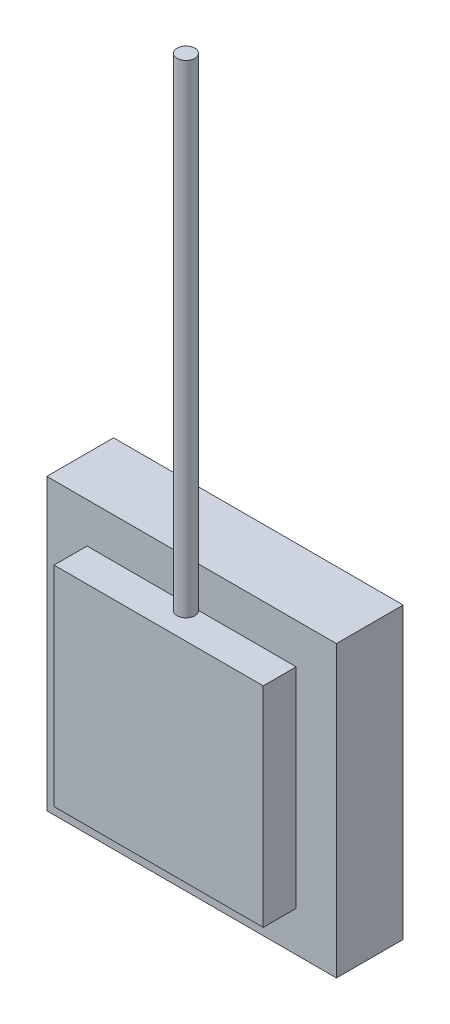
SolidWorks part; units mm, degrees
ref_plane "Спереди" through (0, 0, 0) normal (0, 0, 1) x (1, 0, 0)
ref_plane "Сверху" through (0, 0, 0) normal (0, 1, 0) x (1, 0, 0)
ref_plane "Справа" through (0, 0, 0) normal (1, 0, 0) x (0, 0, -1)
sketch "Sketch1" plane through (0, 0, 0) normal (0, 0, 1) x (1, 0, 0)
  line L1 (0, 0) -> (18, 0)
  line L2 (0, 0) -> (0, 18)
  line L3 (0, 18) -> (18, 18)
  line L4 (18, 0) -> (18, 18)
  dimension "D1" = 18
  dimension "D2" = 18
extrude "Boss-Extrude1" add sketch "Sketch1" along normal blind 4.15
sketch "Sketch2" plane through (0, 0, 4.15) normal (0, 0, 1) x (1, 0, 0)
  line L0 (2.5, 15.5) -> (15.5, 15.5)
  line L1 (0, 18) -> (18, 18) construction
  line L2 (0, 18) -> (0, 0) construction
  line L3 (0, 0) -> (18, 0) construction
  line L4 (18, 18) -> (18, 0) construction
  line L5 (15.5, 15.5) -> (15.5, 2.5)
  line L6 (2.5, 2.5) -> (15.5, 2.5)
  line L7 (2.5, 15.5) -> (2.5, 2.5)
  dimension "D1" = 13
  dimension "D2" = 13
extrude "Boss-Extrude2" add sketch "Sketch2" along normal blind 2.05
sketch "Sketch3" plane through (0, 0, 0) normal (0, 0, -1) x (-1, 0, 0)
  line L0 (-18, 18) -> (0, 18) construction
  line L6 (-18, 0) -> (-18, 18) construction
  line L7 (-9, 18) -> (-9, 0) construction
  line L8 (0, 0) -> (-18, 0) construction
  circle A0 centre (-10, 9) radius 1.5
  dimension "D1" = 3
  dimension "D2" = 9
  dimension "D3" = 8
extrude "Boss-Extrude3" add sketch "Sketch3" along normal blind 0.5
sketch "Sketch4" plane through (0, 15.5, 0) normal (0, 1, 0) x (1, 0, 0)
  circle A0 centre (9.0496, -4.5516) radius 0.5516
extrude "Boss-Extrude4" add sketch "Sketch4" along normal blind 30
